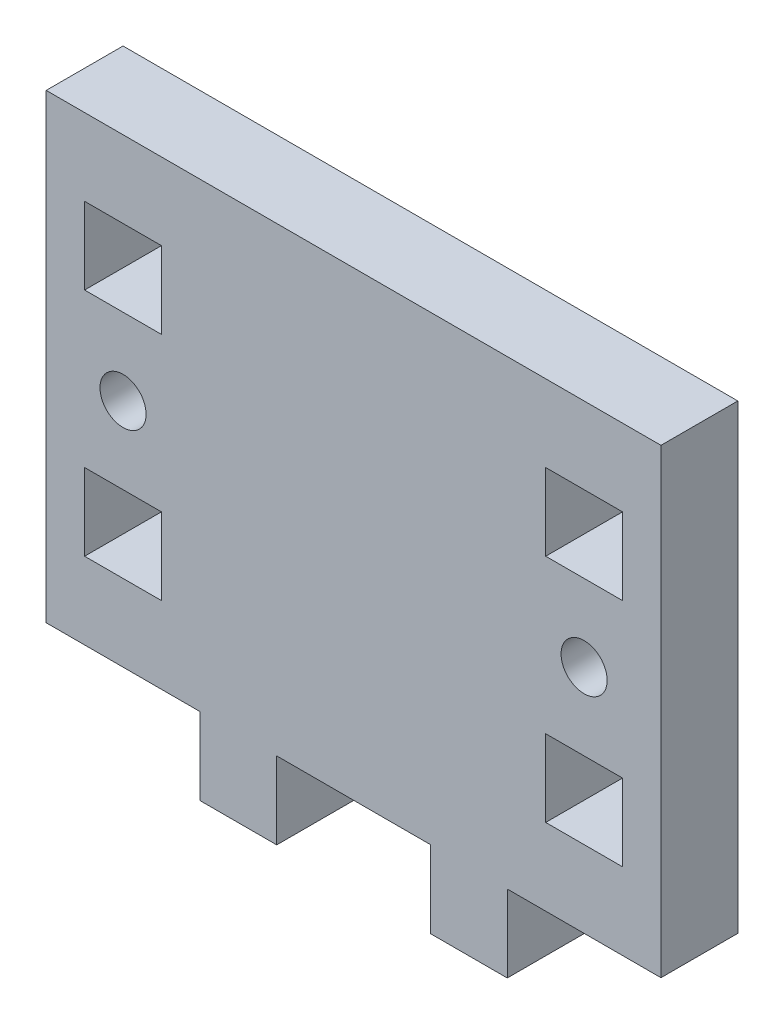
SolidWorks part; units mm, degrees
ref_plane "Front Plane" through (0, 0, 0) normal (0, 0, 1) x (1, 0, 0)
ref_plane "Top Plane" through (0, 0, 0) normal (0, 1, 0) x (1, 0, 0)
ref_plane "Right Plane" through (0, 0, 0) normal (1, 0, 0) x (0, 0, -1)
sketch "Sketch1" plane through (0, 0, 0) normal (0, 0, 1) x (1, 0, 0)
  line L0 (0, 0) -> (0, 5.0154)
  line L1 (0, 5.0154) -> (-10, 5.0154)
  line L2 (-10, 5.0154) -> (-10, 0)
  line L3 (-10, 0) -> (-15, 0)
  line L4 (-15, 0) -> (-15, 5.0154)
  line L5 (-15, 5.0154) -> (-25, 5.0154)
  line L6 (-25, 5.0154) -> (-25, 35.0154)
  line L7 (-25, 35.0154) -> (15, 35.0154)
  line L8 (15, 35.0154) -> (15, 5.0154)
  line L9 (15, 5.0154) -> (5, 5.0154)
  line L10 (5, 5.0154) -> (5, 0)
  line L11 (5, 0) -> (0, 0)
  line L12 (-5, 41.9705) -> (-5, -5.7911) construction
  point P15 (-5, 35.0154)
  line B0 (-20, 15.0154) -> (-20, 25.0154) construction
  line B1 (-22.5, 15.0154) -> (-22.5, 10.0154)
  line B2 (-22.5, 15.0154) -> (-17.5, 15.0154)
  line B3 (-17.5, 15.0154) -> (-17.5, 10.0154)
  line B4 (-22.5, 10.0154) -> (-17.5, 10.0154)
  line B5 (-22.5, 25.0154) -> (-22.5, 30.0154)
  line B6 (-22.5, 25.0154) -> (-17.5, 25.0154)
  line B7 (-17.5, 25.0154) -> (-17.5, 30.0154)
  line B8 (-22.5, 30.0154) -> (-17.5, 30.0154)
  line B9 (-20, 20.0154) -> (-26.2802, 20.0154) construction
  circle B10 centre (-20, 20.0154) radius 1.5
  line B11 (10, 15.0154) -> (10, 25.0154) construction
  line B12 (7.5, 15.0154) -> (7.5, 10.0154)
  line B13 (7.5, 15.0154) -> (12.5, 15.0154)
  line B14 (12.5, 15.0154) -> (12.5, 10.0154)
  line B15 (7.5, 10.0154) -> (12.5, 10.0154)
  line B16 (7.5, 25.0154) -> (7.5, 30.0154)
  line B17 (7.5, 25.0154) -> (12.5, 25.0154)
  line B18 (12.5, 25.0154) -> (12.5, 30.0154)
  line B19 (7.5, 30.0154) -> (12.5, 30.0154)
  line B20 (10, 20.0154) -> (3.7198, 20.0154) construction
  circle B21 centre (10, 20.0154) radius 1.5
  dimension "D1" = 5
  dimension "D2" = 10
  dimension "D3" = 10
  dimension "D4" = 30
  dimension "D5" = 15
  dimension "D6" = 30
sketch_block_instance "Trou M3 plots 5mm-52"
sketch_block "Trou M3 plots 5mm" parameters "D2"=3, "D1"=5, "D3"=5, "D4"=8
sketch_block_instance "Trou M3 plots 5mm-53"
extrude "Boss-Extrude1" add sketch "Sketch1" along normal blind 5
